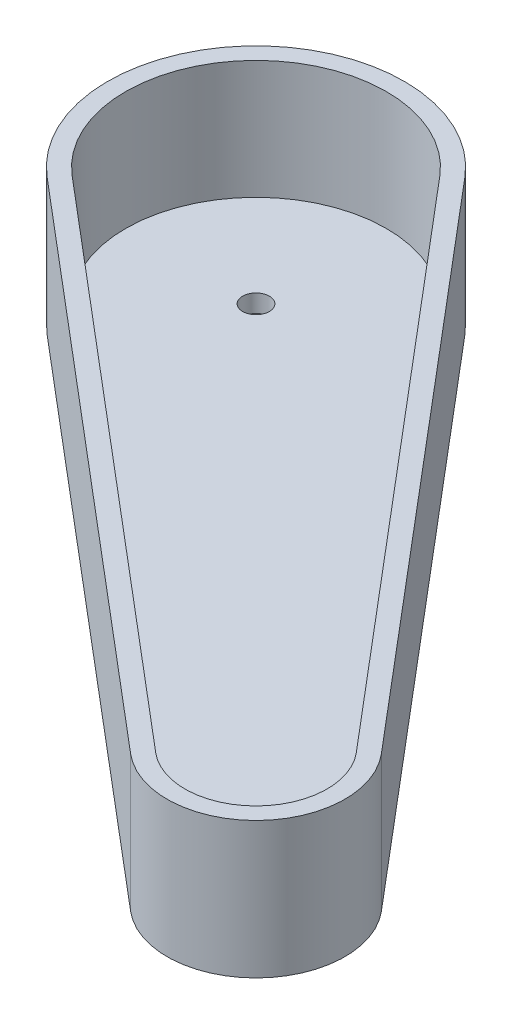
SolidWorks part; units mm, degrees
ref_plane "前视基准面" through (0, 0, 0) normal (0, 0, 1) x (1, 0, 0)
ref_plane "上视基准面" through (0, 0, 0) normal (0, 1, 0) x (1, 0, 0)
ref_plane "右视基准面" through (0, 0, 0) normal (1, 0, 0) x (0, 0, -1)
other "Configuration Table"
sketch "草图2" plane through (0, 0, 0) normal (0, 1, 0) x (1, 0, 0)
  line L0 (-140.5033, 0) -> (6884.6605, 0) construction
  line L1 (0, -140.5033) -> (0, 6884.6605) construction
  line L2 (0, 0) -> (42.4264, -42.4264)
  line L3 (42.4264, -42.4264) -> (-42.4264, 42.4264)
  line L4 (-58.5694, 23.3371) -> (32.7406, -53.88)
  line L5 (-23.3371, 58.5694) -> (53.88, -32.7406)
  circle A0 centre (-42.4264, 42.4264) radius 25
  circle A1 centre (42.4264, -42.4264) radius 15
  dimension "D3" = 50
  dimension "D4" = 30
  dimension "D1" = 60
  dimension "D2" = 120
extrude "凸台-拉伸2" add sketch "草图2" along normal blind 3
sketch "草图4" plane through (0, 3, 0) normal (0, 1, 0) x (1, 0, 0)
  line L0 (-58.5694, 23.3371) -> (32.7406, -53.88)
  line L1 (-58.5694, 23.3371) -> (32.7406, -53.88) construction
  line L2 (-23.3371, 58.5694) -> (53.88, -32.7406)
  line L3 (-23.3371, 58.5694) -> (53.88, -32.7406) construction
  line L4 (-56.6323, 25.6278) -> (34.6777, -51.5893)
  line L5 (-25.6278, 56.6323) -> (51.5893, -34.6777)
  circle A0 centre (-42.4264, 42.4264) radius 25
  circle A1 centre (42.4264, -42.4264) radius 15
  circle A2 centre (-42.4264, 42.4264) radius 22
  circle A3 centre (42.4264, -42.4264) radius 12
  line M3 (-58.5694, 23.3371) -> (32.7406, -53.88)
  arc M4 (32.7406, -53.88) -> (53.88, -32.7406) centre (42.4264, -42.4264) ccw
  line M5 (53.88, -32.7406) -> (-23.3371, 58.5694)
  arc M6 (-23.3371, 58.5694) -> (-58.5694, 23.3371) centre (-42.4264, 42.4264) ccw
  dimension "D1" = 3
  dimension "D2" = 3
extrude "凸台-拉伸3" add sketch "草图4" along normal blind 20 contours A1 L4 A0 M3 | A2 L5 A0 L4 M6 | A1 A0 L5 M5 | A3 L4 A1 L5 M4
sketch "草图5" plane through (0, 3, 0) normal (0, 1, 0) x (1, 0, 0)
  circle A0 centre (-42.4264, 42.4264) radius 2.25
  circle A1 centre (42.4264, -42.4264) radius 2.5
  dimension "D1" = 4.5
  dimension "D2" = 5
extrude "切除-拉伸1" cut sketch "草图5" against normal through all
